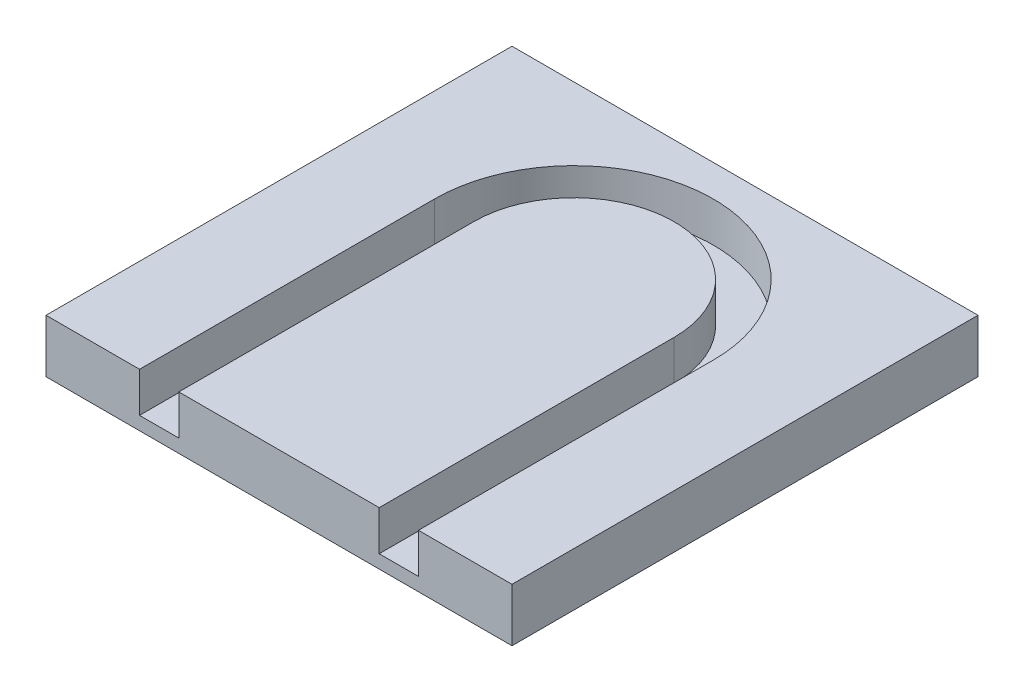
SolidWorks part; units mm, degrees
ref_plane "Front Plane" through (0, 0, 0) normal (0, 0, 1) x (1, 0, 0)
ref_plane "Top Plane" through (0, 0, 0) normal (0, 1, 0) x (1, 0, 0)
ref_plane "Right Plane" through (0, 0, 0) normal (1, 0, 0) x (0, 0, -1)
sketch "Sketch1" plane through (0, 0, 0) normal (0, 1, 0) x (1, 0, 0)
  line L5 (-17.5, -17.5) -> (17.5, -17.5)
  line L6 (-17.5, -17.5) -> (-17.5, 17.5)
  line L7 (-17.5, 17.5) -> (17.5, 17.5)
  line L8 (17.5, -17.5) -> (17.5, 17.5)
  line L9 (-17.5, -17.5) -> (17.5, 17.5) construction
  line L10 (-17.5, 17.5) -> (17.5, -17.5) construction
  point P0 (0, 0)
  dimension "D1" = 35
  dimension "D2" = 35
extrude "Boss-Extrude1" add sketch "Sketch1" along normal blind 1
sketch "Sketch2" plane through (0, 1, 0) normal (0, 1, 0) x (1, 0, 0)
  line L0 (0, 17.5) -> (0, -17.5) construction
  line L1 (17.5, 17.5) -> (-17.5, 17.5) construction
  line L2 (-17.5, -17.5) -> (17.5, -17.5) construction
  line L3 (-9, 4.6504) -> (-9, -17.5) construction
  line L4 (9, 4.6504) -> (9, -17.5) construction
  line L5 (-10.475, -17.5) -> (-10.475, 4.6504)
  line L6 (-7.525, -17.5) -> (-7.525, 4.6504)
  line L7 (7.525, -17.5) -> (7.525, 4.6504)
  line L8 (10.475, -17.5) -> (10.475, 4.6504)
  line L9 (-10.475, -17.5) -> (-7.525, -17.5)
  line L10 (7.525, -17.5) -> (10.475, -17.5)
  line L12 (-17.5, 17.5) -> (17.5, 17.5)
  line L13 (-17.5, 17.5) -> (-17.5, -17.5)
  line L14 (-17.5, -17.5) -> (17.5, -17.5)
  line L15 (17.5, 17.5) -> (17.5, -17.5)
  circle A0 centre (0, 4.6504) radius 9 construction
  arc A1 (7.525, 4.6504) -> (-7.525, 4.6504) centre (0, 4.6504) ccw
  arc A2 (10.475, 4.6504) -> (-10.475, 4.6504) centre (0, 4.6504) ccw
  line M5 (17.5, -17.5) -> (17.5, 17.5)
  line M6 (17.5, 17.5) -> (-17.5, 17.5)
  line M7 (-17.5, 17.5) -> (-17.5, -17.5)
  line M8 (-17.5, -17.5) -> (17.5, -17.5)
  dimension "D1" = 18
  dimension "D2" = 2.95
  dimension "D3" = 12.8496
extrude "Boss-Extrude2" add sketch "Sketch2" along normal blind 3 contours A2 L8 L5 M8 M5 M6 M7 | L7 A1 L6 M8
